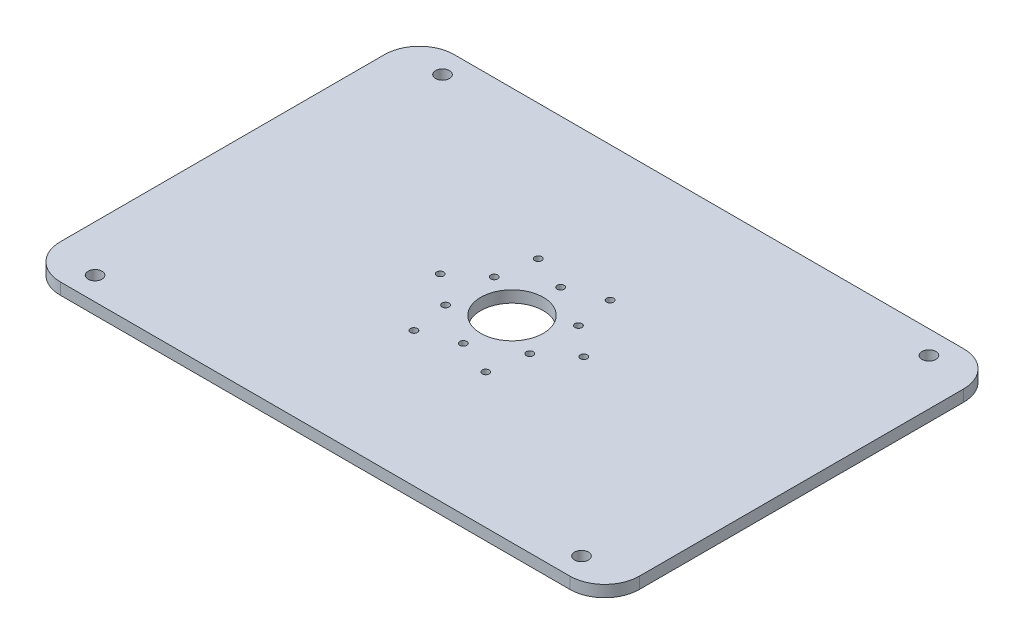
SolidWorks part; units mm, degrees
ref_plane "前视基准面" through (0, 0, 0) normal (0, 0, 1) x (1, 0, 0)
ref_plane "上视基准面" through (0, 0, 0) normal (0, 1, 0) x (1, 0, 0)
ref_plane "右视基准面" through (0, 0, 0) normal (1, 0, 0) x (0, 0, -1)
other "Configuration Table"
sketch "草图1" plane through (0, 0, 0) normal (0, 1, 0) x (1, 0, 0)
  line L1 (-125, -85) -> (125, -85)
  line L2 (-125, -85) -> (-125, 85)
  line L3 (-125, 85) -> (125, 85)
  line L4 (125, -85) -> (125, 85)
  line L5 (0, 85) -> (0, -85) construction
  line L6 (-125, 0) -> (125, 0) construction
  circle A0 centre (-105, 75) radius 3
  circle A1 centre (105, 75) radius 3
  circle A2 centre (-105, -75) radius 3
  circle A3 centre (105, -75) radius 3
  dimension "D1" = 6
  dimension "D2" = 150
  dimension "D3" = 210
  dimension "D4" = 250
  dimension "D5" = 170
extrude "凸台-拉伸1" add sketch "草图1" along normal blind 5
fillet "圆角1" radius 15 4 edges at (125, 2.5, 85) (125, 2.5, -85) (-125, 2.5, -85) (-125, 2.5, 85)
sketch "草图2" plane through (0, 0, 0) normal (0, 1, 0) x (1, 0, 0)
  line L0 (-160.4139, 0) -> (155.4702, 0) construction
  line L1 (0, 98.9588) -> (0, -103.2206) construction
  line L2 (0, 0) -> (0, 21) construction
  line L3 (0, 0) -> (18.1865, 10.5) construction
  circle A5 centre (0, 0) radius 21 construction
  circle A6 centre (0, 21) radius 1.5
  circle A7 centre (18.1865, 10.5) radius 1.5
  circle A8 centre (18.1865, -10.5) radius 1.5
  circle A9 centre (0, -21) radius 1.5
  circle A10 centre (-18.1865, -10.5) radius 1.5
  circle A11 centre (-18.1865, 10.5) radius 1.5
  circle A12 centre (0, 0) radius 31 construction
  circle A13 centre (31, 0) radius 1.5
  circle A14 centre (15.5, -26.8468) radius 1.5
  circle A15 centre (-15.5, -26.8468) radius 1.5
  circle A16 centre (-31, 0) radius 1.5
  circle A17 centre (-15.5, 26.8468) radius 1.5
  circle A18 centre (15.5, 26.8468) radius 1.5
  circle A19 centre (0, 0) radius 13.5
  point P37 (0, 0)
  dimension "D2" = 3
  dimension "D1" = 42
  dimension "D3" = 6
  dimension "D5" = 62
  dimension "D6" = 3
  dimension "D8" = 27
  dimension "D4" = 60
  dimension "D7" = 6
extrude "切除-拉伸1" cut sketch "草图2" along normal through all
